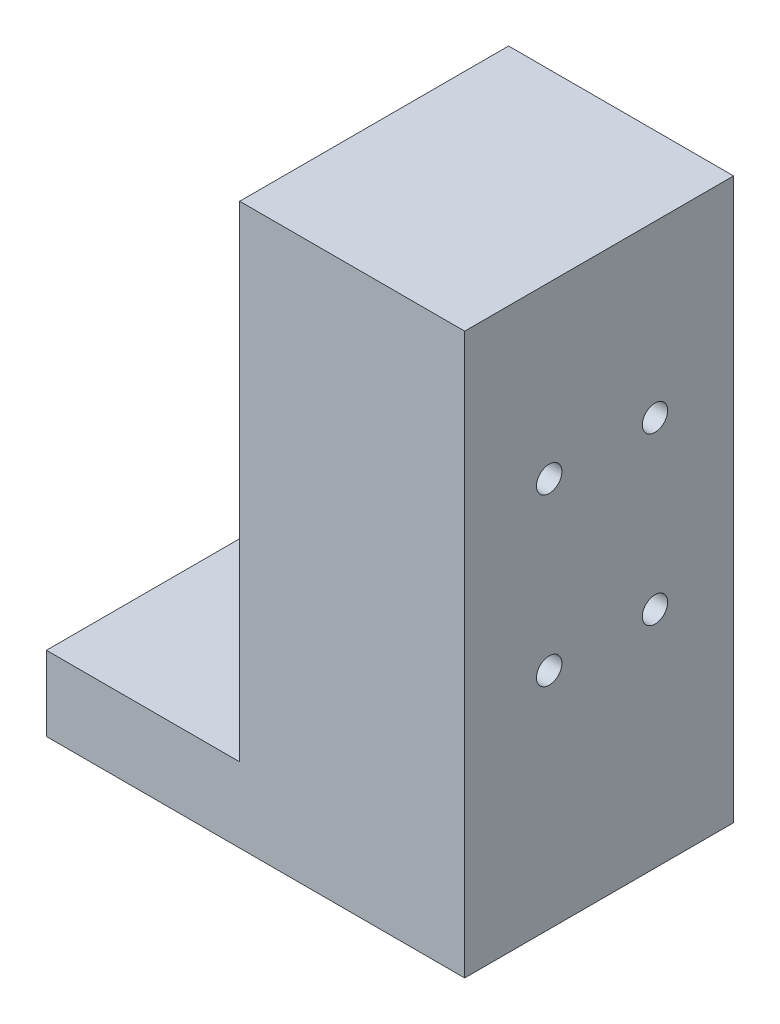
SolidWorks part; units mm, degrees
ref_plane "Front Plane" through (0, 0, 0) normal (0, 0, 1) x (1, 0, 0)
ref_plane "Top Plane" through (0, 0, 0) normal (0, 1, 0) x (1, 0, 0)
ref_plane "Right Plane" through (0, 0, 0) normal (1, 0, 0) x (0, 0, -1)
sketch "Sketch1" plane through (0, 0, 0) normal (0, 0, 1) x (1, 0, 0)
  line L0 (-42.6182, 0.2333) -> (-42.6182, -9.7667)
  line L1 (-42.6182, -9.7667) -> (13.3818, -9.7667)
  line L2 (13.3818, -9.7667) -> (13.3818, 65.2333)
  line L3 (13.3818, 65.2333) -> (-16.7428, 65.2333)
  line L4 (-16.7428, 65.2333) -> (-16.7428, 0.2333)
  line L5 (-16.7428, 0.2333) -> (-42.6182, 0.2333)
extrude "Boss-Extrude1" add sketch "Sketch1" along normal blind 36
sketch "Sketch2" plane through (0, 0.2333, 0) normal (0, 1, 0) x (1, 0, 0)
  circle A0 centre (-29.6805, -18) radius 2.625
  dimension "D1" = 5.25
extrude "Cut-Extrude1" cut sketch "Sketch2" against normal through all
sketch "Sketch3" plane through (13.3818, 0, 0) normal (1, 0, 0) x (0, 0, -1)
  line L0 (-36, 65.2333) -> (0, 65.2333) construction
  circle A0 centre (-24.6876, 20.2333) radius 1.7
  circle A1 centre (-10.5201, 20.2333) radius 1.7
  circle A2 centre (-24.6876, 42.4611) radius 1.7
  circle A3 centre (-10.5201, 42.4611) radius 1.7
  dimension "D2" = 3.4
  dimension "D3" = 3.4
  dimension "D4" = 3.4
  dimension "D5" = 3.4
  dimension "D1" = 45
extrude "Cut-Extrude2" cut sketch "Sketch3" against normal through all and the other way through all
